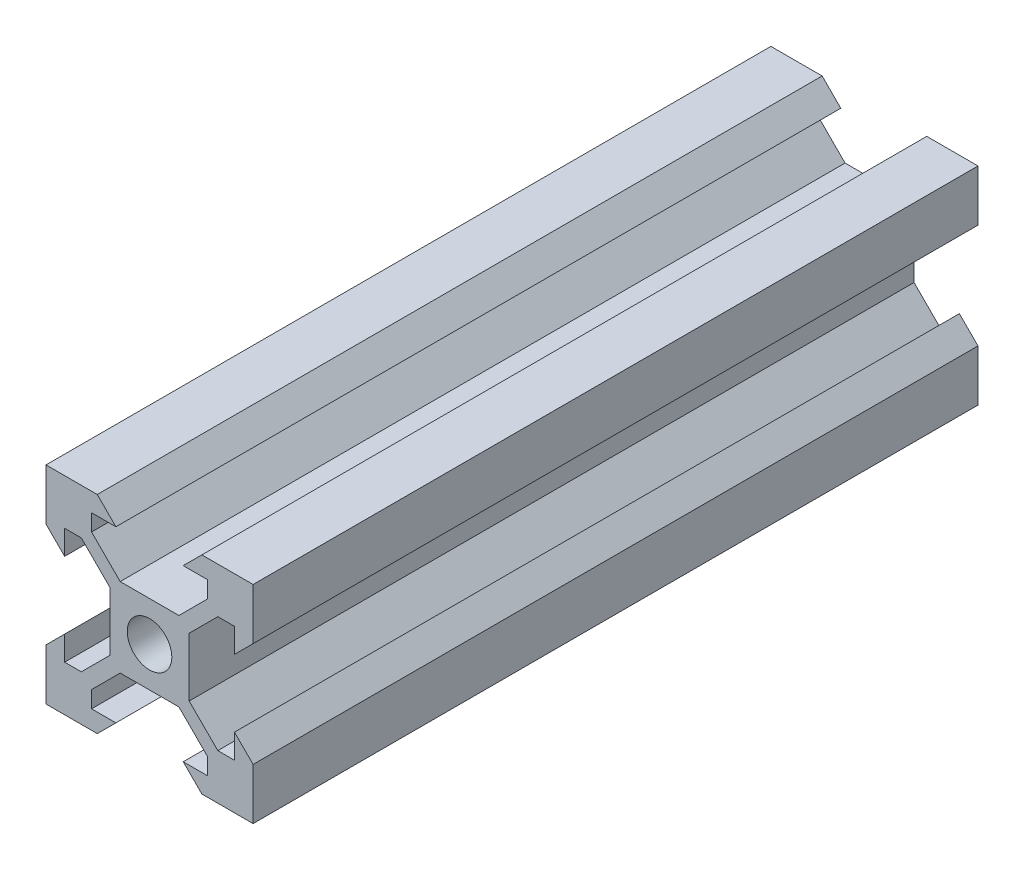
SolidWorks part; units mm, degrees
ref_plane "Alzado" through (0, 0, 0) normal (0, 0, 1) x (1, 0, 0)
ref_plane "Planta" through (0, 0, 0) normal (0, 1, 0) x (1, 0, 0)
ref_plane "Vista lateral" through (0, 0, 0) normal (1, 0, 0) x (0, 0, -1)
sketch "Croquis1" plane through (0, 0, 0) normal (0, 0, 1) x (1, 0, 0)
  line L0 (0, 0) -> (0, -20) construction
  line L2 (0, 0) -> (0, -0.5674)
  line L5 (6.175, -7.1649) -> (6.175, -12.8351)
  line L6 (7.1649, -13.825) -> (12.8351, -13.825)
  line L7 (13.825, -7.1649) -> (13.825, -12.8351)
  line L8 (7.1649, -6.175) -> (12.8351, -6.175)
  line L9 (6.175, -13.825) -> (13.825, -13.825) construction
  line L10 (13.825, -6.175) -> (13.825, -13.825) construction
  line L12 (10, -10) -> (32.1172, -10) construction
  line L13 (13.25, -18.2) -> (15.05, -20)
  line L14 (20, -20) -> (15.6, -20)
  line L15 (20, -20) -> (20, -15.6)
  line L16 (18.2, -15.6) -> (16.5899, -15.6)
  line L32 (15.6, -18.2) -> (15.6, -16.5899)
  line L33 (10, -10) -> (10, -23.2493) construction
  line L34 (4.4, -18.2) -> (4.4, -16.5899)
  line L35 (7.1649, -13.825) -> (4.4, -16.5899)
  line L36 (15.6, -18.2) -> (13.25, -18.2)
  line L38 (15.6, -20) -> (15.05, -20)
  line L40 (15.05, -20) -> (20, -20)
  line L41 (0, -20) -> (20, -20) construction
  line L42 (6.175, -12.8351) -> (3.4101, -15.6)
  line L43 (18.2, -13.25) -> (20, -15.05)
  line L44 (20, -20) -> (18.2, -20)
  line L45 (20, -20) -> (20, -15.05)
  line L48 (20, -15.05) -> (20, -20)
  line L49 (20, 0) -> (20, -20) construction
  line L50 (18.2, -15.6) -> (18.2, -13.25)
  line L51 (12.8351, -13.825) -> (15.6, -16.5899)
  line L52 (13.825, -12.8351) -> (16.5899, -15.6)
  line L53 (1.8, -15.6) -> (3.4101, -15.6)
  line L54 (1.8, -15.6) -> (1.8, -13.25)
  line L55 (1.8, -13.25) -> (0, -15.05)
  line L56 (0, 0) -> (20, 0) construction
  line L57 (0, -20) -> (0, -15.6)
  line L58 (0, -15.6) -> (0, -15.05)
  line L59 (0, -20) -> (4.4, -20)
  line L60 (0, -20) -> (4.95, -20)
  line L61 (6.75, -18.2) -> (4.95, -20)
  line L62 (4.4, -18.2) -> (6.75, -18.2)
  line L63 (1.8, -4.4) -> (3.4101, -4.4)
  line L64 (6.175, -7.1649) -> (3.4101, -4.4)
  line L65 (7.1649, -6.175) -> (4.4, -3.4101)
  line L66 (4.4, -1.8) -> (4.4, -3.4101)
  line L67 (4.4, -1.8) -> (6.75, -1.8)
  line L68 (6.75, -1.8) -> (4.95, 0)
  line L69 (0, 0) -> (4.4, 0)
  line L70 (4.4, 0) -> (4.95, 0)
  line L71 (0, 0) -> (0, -4.4)
  line L72 (0, 0) -> (0, -4.95)
  line L73 (1.8, -6.75) -> (0, -4.95)
  line L74 (1.8, -4.4) -> (1.8, -6.75)
  line L75 (15.6, -1.8) -> (15.6, -3.4101)
  line L76 (12.8351, -6.175) -> (15.6, -3.4101)
  line L77 (13.825, -7.1649) -> (16.5899, -4.4)
  line L78 (18.2, -4.4) -> (16.5899, -4.4)
  line L79 (18.2, -4.4) -> (18.2, -6.75)
  line L80 (18.2, -6.75) -> (20, -4.95)
  line L81 (20, 0) -> (20, -4.4)
  line L82 (20, -4.4) -> (20, -4.95)
  line L83 (20, 0) -> (15.6, 0)
  line L84 (20, 0) -> (15.05, 0)
  line L85 (13.25, -1.8) -> (15.05, 0)
  line L86 (15.6, -1.8) -> (13.25, -1.8)
  line L87 (6.175, -6.175) -> (13.825, -6.175) construction
  line L88 (6.175, -6.175) -> (6.175, -13.825) construction
  circle A0 centre (10, -10) radius 2.15
  point P69 (10, -10)
  dimension "D3" = 4.3
  dimension "D2" = 4
  dimension "D11" = 4.4
  dimension "D15" = 4.4
  dimension "D16" = 6.75
extrude "Saliente-Extruir2" add sketch "Croquis1" along normal blind 70 contours L86 L75 L76 L8 L65 L66 L67 L68 L70 L69 L2 L71 L72 L73 L74 L63 L64 L5 L42 L53 L54 L55 L58 L57 L59 L60 L61 L62 L34 L35 L6 L51 L32 L36 L13 L38 L40 L14 L15 L45 L43 L50 L16 L52 L7 L77 L78 L79 L80 L82 L81
